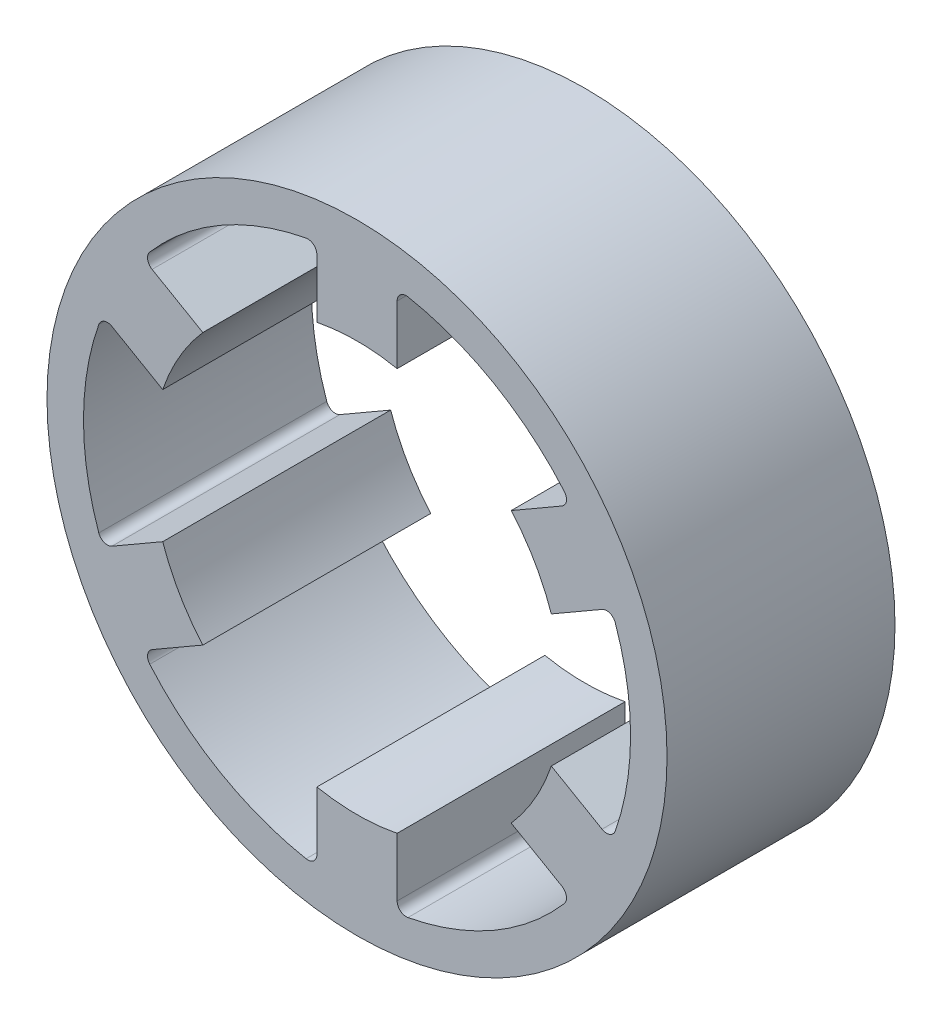
SolidWorks part; units mm, degrees
material "1023 Листовая углеродистая сталь (SS)"
ref_plane "Спереди" through (0, 0, 0) normal (0, 0, 1) x (1, 0, 0)
ref_plane "Сверху" through (0, 0, 0) normal (0, 1, 0) x (1, 0, 0)
ref_plane "Справа" through (0, 0, 0) normal (1, 0, 0) x (0, 0, -1)
sketch "Эскиз1" plane through (0, 0, 0) normal (1, 0, 0) x (0, 0, -1)
  line L0 (0, 0) -> (50, 0) construction
  line L1 (50, 0) -> (50, 45) construction
  line L2 (50, 45) -> (0, 45) construction
  line L3 (0, 45) -> (0, 0) construction
  line L4 (0, 45) -> (50, 45)
  line L5 (50, 45) -> (50, 68)
  line L6 (50, 68) -> (0, 68)
  line L7 (0, 68) -> (0, 45)
  dimension "D1" = 90
  dimension "D2" = 136
  dimension "D3" = 50
revolve "Повернуть1" add sketch "Эскиз1" angle 360 about L0
sketch "Эскиз2" plane through (0, 0, 0) normal (0, 0, 1) x (1, 0, 0)
  line L0 (0, 0) -> (0, 60) construction
  line L1 (0, 0) -> (68, 0) construction
  line L2 (68, 0) -> (68, 60) construction
  line L3 (68, 60) -> (0, 60) construction
  line L4 (0, 0) -> (34, 58.8897) construction
  line L5 (0, 45) -> (68, 45) construction
  line L6 (-8.8, 59.3512) -> (-8.8, 44.1312)
  line L7 (-34, 58.8897) -> (0, 0) construction
  line L8 (8.8, 59.3512) -> (8.8, 44.1312)
  line L9 (-30, 51.9615) -> (-22.5, 38.9711)
  line L10 (22.5, 38.9711) -> (30, 51.9615)
  circle A0 centre (0, 0) radius 68 construction
  circle A1 centre (0, 0) radius 45 construction
  circle A2 centre (0, 0) radius 60 construction
  arc A3 (-22.5, 38.9711) -> (-8.8, 44.1312) centre (0, 0) cw
  arc A4 (-30, 51.9615) -> (-8.8, 59.3512) centre (0, 0) cw
  arc A5 (8.8, 44.1312) -> (22.5, 38.9711) centre (0, 0) cw
  arc A6 (8.8, 59.3512) -> (30, 51.9615) centre (0, 0) cw
  dimension "D1" = 15
  dimension "D2" = 60
  dimension "D3" = 17.6
extrude "Вырез-Вытянуть1" cut sketch "Эскиз2" against normal through all
fillet "Скругление1" radius 2 2 edges at (8.8, 59.3512, -25) (-8.8, 59.3512, -25)
pattern_circular "Круговой массив1" count 6 over 360 about axis through (0, 0, 0) along (0, 0, 1) of "Вырез-Вытянуть1", "Скругление1"
